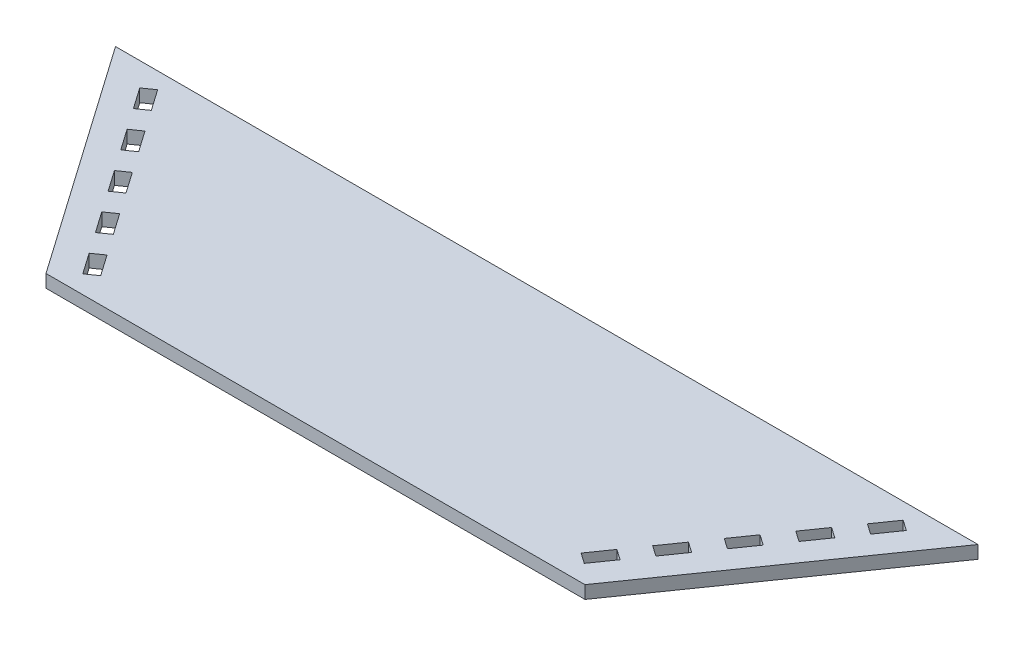
SolidWorks part; units mm, degrees
material "Acrylic (Medium-high impact)"
ref_plane "Front Plane" through (0, 0, 0) normal (0, 0, 1) x (1, 0, 0)
ref_plane "Top Plane" through (0, 0, 0) normal (0, 1, 0) x (1, 0, 0)
ref_plane "Right Plane" through (0, 0, 0) normal (1, 0, 0) x (0, 0, -1)
sketch "Sketch1" plane through (0, 0, 0) normal (0, 1, 0) x (1, 0, 0)
  line L0 (0, 0) -> (-70.625, 100.975) construction
  line L1 (-39.9725, 57.15) -> (173.1519, 57.15)
  line L2 (66.5897, 57.15) -> (66.5897, 0) construction
  line L3 (133.1794, 0) -> (0, 0)
  line L4 (0, 0) -> (-70.625, 0) construction
  line L5 (-70.625, 0) -> (-70.625, 100.975) construction
  line L6 (0, 0) -> (-39.9725, 57.15)
  line L7 (-18.2457, 42.7052) -> (-14.6062, 37.5017)
  line L8 (-18.2457, 42.7052) -> (-20.8475, 40.8855)
  line L9 (-20.8475, 40.8855) -> (-17.208, 35.682)
  line L10 (-14.6062, 37.5017) -> (-17.208, 35.682)
  line L11 (-10.9667, 32.2982) -> (-13.5685, 30.4785)
  line L12 (-9.929, 25.275) -> (-13.5685, 30.4785)
  line L13 (-7.3272, 27.0947) -> (-9.929, 25.275)
  line L14 (-7.3272, 27.0947) -> (-10.9667, 32.2982)
  line L15 (-0.0482, 16.6877) -> (-2.65, 14.8679)
  line L16 (-3.6877, 21.8912) -> (-0.0482, 16.6877)
  line L17 (-3.6877, 21.8912) -> (-6.2895, 20.0714)
  line L18 (-6.2895, 20.0714) -> (-2.65, 14.8679)
  line L19 (3.5913, 11.4842) -> (0.9895, 9.6644)
  line L20 (4.629, 4.4609) -> (0.9895, 9.6644)
  line L21 (7.2308, 6.2806) -> (4.629, 4.4609)
  line L22 (7.2308, 6.2806) -> (3.5913, 11.4842)
  line L23 (133.1794, 0) -> (173.1519, 57.15)
  line L24 (155.0646, 47.9088) -> (157.6664, 46.089)
  line L25 (161.3059, 51.2925) -> (157.6664, 46.089)
  line L26 (158.7041, 53.1123) -> (161.3059, 51.2925)
  line L27 (158.7041, 53.1123) -> (155.0646, 47.9088)
  line L28 (125.9487, 6.2806) -> (129.5882, 11.4842)
  line L29 (125.9487, 6.2806) -> (128.5504, 4.4609)
  line L30 (128.5504, 4.4609) -> (132.1899, 9.6644)
  line L31 (129.5882, 11.4842) -> (132.1899, 9.6644)
  line L32 (139.4689, 20.0714) -> (135.8294, 14.8679)
  line L33 (136.8672, 21.8912) -> (139.4689, 20.0714)
  line L34 (136.8672, 21.8912) -> (133.2277, 16.6877)
  line L35 (133.2277, 16.6877) -> (135.8294, 14.8679)
  line L36 (140.5067, 27.0947) -> (144.1461, 32.2982)
  line L37 (140.5067, 27.0947) -> (143.1084, 25.275)
  line L38 (143.1084, 25.275) -> (146.7479, 30.4785)
  line L39 (144.1461, 32.2982) -> (146.7479, 30.4785)
  line L40 (-25.5247, 53.1123) -> (-21.8852, 47.9088)
  line L41 (-25.5247, 53.1123) -> (-28.1265, 51.2925)
  line L42 (-28.1265, 51.2925) -> (-24.487, 46.089)
  line L43 (-21.8852, 47.9088) -> (-24.487, 46.089)
  line L44 (147.7856, 37.5017) -> (150.3874, 35.682)
  line L45 (154.0269, 40.8855) -> (150.3874, 35.682)
  line L46 (151.4251, 42.7052) -> (154.0269, 40.8855)
  line L47 (151.4251, 42.7052) -> (147.7856, 37.5017)
  dimension "D1" = 70.625
  dimension "D2" = 100.975
  dimension "D3" = 3.175
  dimension "D4" = 6.35
  dimension "D5" = 4.0377
  dimension "D6" = 6.35
  dimension "D7" = 6.35
  dimension "D8" = 6.35
  dimension "D9" = 6.35
  dimension "D11" = 57.15
  dimension "D12" = 61.9607
  dimension "D13" = 6.35
extrude "Boss-Extrude1" add sketch "Sketch1" along normal blind 3.175
